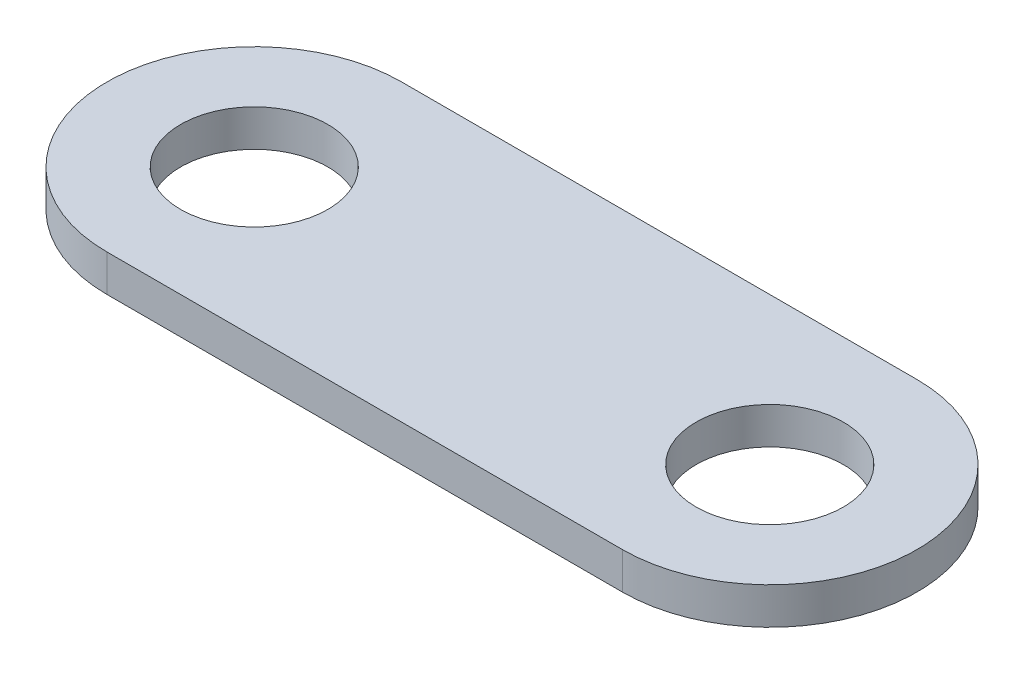
SolidWorks part; units mm, degrees
ref_plane "Front Plane" through (0, 0, 0) normal (0, 0, 1) x (1, 0, 0)
ref_plane "Top Plane" through (0, 0, 0) normal (0, 1, 0) x (1, 0, 0)
ref_plane "Right Plane" through (0, 0, 0) normal (1, 0, 0) x (0, 0, -1)
sketch "Sketch1" plane through (0, 0, 0) normal (0, 1, 0) x (1, 0, 0)
  line L0 (0, 0) -> (44.45, 0) construction
  line L1 (0, 12.7) -> (44.45, 12.7)
  line L2 (0, -12.7) -> (44.45, -12.7)
  arc A0 (0, 12.7) -> (0, -12.7) centre (0, 0) ccw
  arc A1 (44.45, -12.7) -> (44.45, 12.7) centre (44.45, 0) ccw
  circle A2 centre (0, 0) radius 6.35
  circle A3 centre (44.45, 0) radius 6.35
  point P3 (22.225, 0)
  dimension "D2" = 12.7
  dimension "D3" = 12.7
  dimension "D4" = 12.7
  dimension "D1" = 44.45
extrude "Boss-Extrude1" add sketch "Sketch1" along normal blind 3.175
